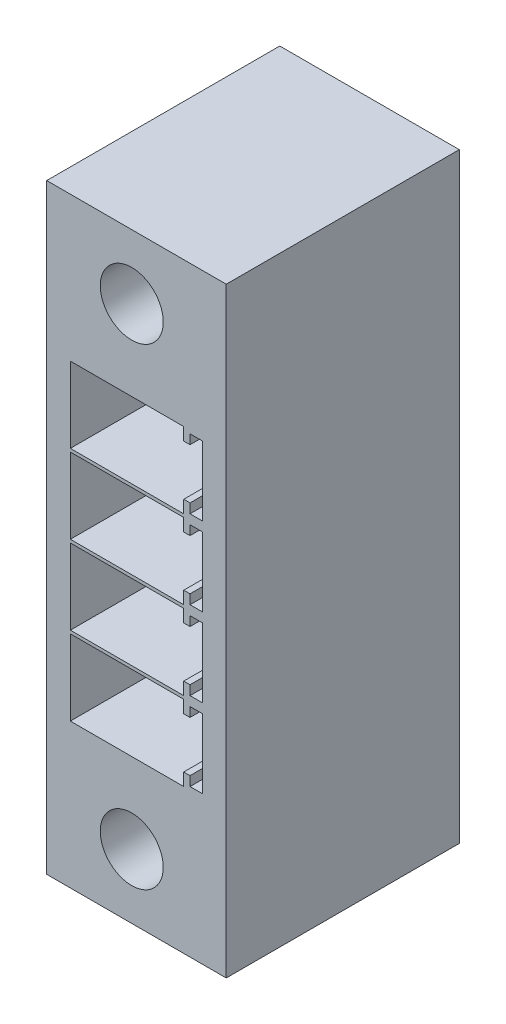
SolidWorks part; units mm, degrees
ref_plane "Front Plane" through (0, 0, 0) normal (0, 0, 1) x (1, 0, 0)
ref_plane "Top Plane" through (0, 0, 0) normal (0, 1, 0) x (1, 0, 0)
ref_plane "Right Plane" through (0, 0, 0) normal (1, 0, 0) x (0, 0, -1)
ref_plane "Plane1" through (3.6195, 0, 0) normal (1, 0, 0) x (0, 0, -1)
sketch "Sketch1" plane through (3.6195, 0, 0) normal (1, 0, 0) x (0, 0, -1)
  line L0 (4.699, -12.1158) -> (4.699, 12.1158)
  line L1 (4.699, 12.1158) -> (-4.699, 12.1158)
  line L2 (-4.699, 12.1158) -> (-4.699, -12.1158)
  line L3 (-4.699, -12.1158) -> (4.699, -12.1158)
extrude "Boss-Extrude1" add sketch "Sketch1" against normal blind 7.239
hole_wizard "Hole1" positions "Sketch3" profile "Sketch2" legacy
sketch "Sketch3" plane through (0, 0, 4.699) normal (0, 0, 1) x (1, 0, 0)
  point P0 (-0.1905, -9.525)
  point P1 (-0.1905, 9.525)
sketch "Sketch2" plane through (-0.1905, -9.525, 4.699) normal (1, 0, 0) x (0, -1, 0)
  line L0 (0, 0) -> (0, 7.1131)
  line L1 (0, 7.1131) -> (1.27, 6.35)
  line L2 (1.27, 6.35) -> (1.27, 0)
  line L4 (1.27, 0) -> (0, 0)
  line L6 (0, 7.1131) -> (-1.27, 6.35) construction
  line L7 (0, -4.2442) -> (0, 117.3081) construction
  dimension "Diameter" = 2.54
  dimension "Depth" = 6.35
  dimension "Drill Angle" = 118
ref_plane "Plane2" through (0, 0, -1.651) normal (0, 0, -1) x (-1, 0, 0)
sketch "Sketch4" plane through (0, 0, -1.651) normal (0, 0, -1) x (-1, 0, 0)
  line L0 (2.667, 6.2865) -> (-1.905, 6.2865)
  line L1 (-1.905, 6.2865) -> (-1.905, 5.7785)
  line L2 (-1.905, 5.7785) -> (-2.159, 5.7785)
  line L3 (-2.159, 5.7785) -> (-2.159, 6.1595)
  line L4 (-2.159, 6.1595) -> (-2.667, 6.1595)
  line L5 (-2.667, 6.1595) -> (-2.667, 3.3655)
  line L6 (-2.667, 3.3655) -> (-2.159, 3.3655)
  line L7 (-2.159, 3.3655) -> (-2.159, 3.7465)
  line L8 (-2.159, 3.7465) -> (-1.905, 3.7465)
  line L9 (-1.905, 3.7465) -> (-1.905, 3.2385)
  line L10 (-1.905, 3.2385) -> (2.667, 3.2385)
  line L11 (2.667, 3.2385) -> (2.667, 6.2865)
  line L12 (2.667, 3.1115) -> (-1.905, 3.1115)
  line L13 (-1.905, 3.1115) -> (-1.905, 2.6035)
  line L14 (-1.905, 2.6035) -> (-2.159, 2.6035)
  line L15 (-2.159, 2.6035) -> (-2.159, 2.9845)
  line L16 (-2.159, 2.9845) -> (-2.667, 2.9845)
  line L17 (-2.667, 2.9845) -> (-2.667, 0.1905)
  line L18 (-2.667, 0.1905) -> (-2.159, 0.1905)
  line L19 (-2.159, 0.1905) -> (-2.159, 0.5715)
  line L20 (-2.159, 0.5715) -> (-1.905, 0.5715)
  line L21 (-1.905, 0.5715) -> (-1.905, 0.0635)
  line L22 (-1.905, 0.0635) -> (2.667, 0.0635)
  line L23 (2.667, 0.0635) -> (2.667, 3.1115)
  line L24 (2.667, -0.0635) -> (-1.905, -0.0635)
  line L25 (-1.905, -0.0635) -> (-1.905, -0.5715)
  line L26 (-1.905, -0.5715) -> (-2.159, -0.5715)
  line L27 (-2.159, -0.5715) -> (-2.159, -0.1905)
  line L28 (-2.159, -0.1905) -> (-2.667, -0.1905)
  line L29 (-2.667, -0.1905) -> (-2.667, -2.9845)
  line L30 (-2.667, -2.9845) -> (-2.159, -2.9845)
  line L31 (-2.159, -2.9845) -> (-2.159, -2.6035)
  line L32 (-2.159, -2.6035) -> (-1.905, -2.6035)
  line L33 (-1.905, -2.6035) -> (-1.905, -3.1115)
  line L34 (-1.905, -3.1115) -> (2.667, -3.1115)
  line L35 (2.667, -3.1115) -> (2.667, -0.0635)
  line L36 (2.667, -3.2385) -> (-1.905, -3.2385)
  line L37 (-1.905, -3.2385) -> (-1.905, -3.7465)
  line L38 (-1.905, -3.7465) -> (-2.159, -3.7465)
  line L39 (-2.159, -3.7465) -> (-2.159, -3.3655)
  line L40 (-2.159, -3.3655) -> (-2.667, -3.3655)
  line L41 (-2.667, -3.3655) -> (-2.667, -6.1595)
  line L42 (-2.667, -6.1595) -> (-2.159, -6.1595)
  line L43 (-2.159, -6.1595) -> (-2.159, -5.7785)
  line L44 (-2.159, -5.7785) -> (-1.905, -5.7785)
  line L45 (-1.905, -5.7785) -> (-1.905, -6.2865)
  line L46 (-1.905, -6.2865) -> (2.667, -6.2865)
  line L47 (2.667, -6.2865) -> (2.667, -3.2385)
extrude "Cut-Extrude1" cut sketch "Sketch4" against normal up to next
